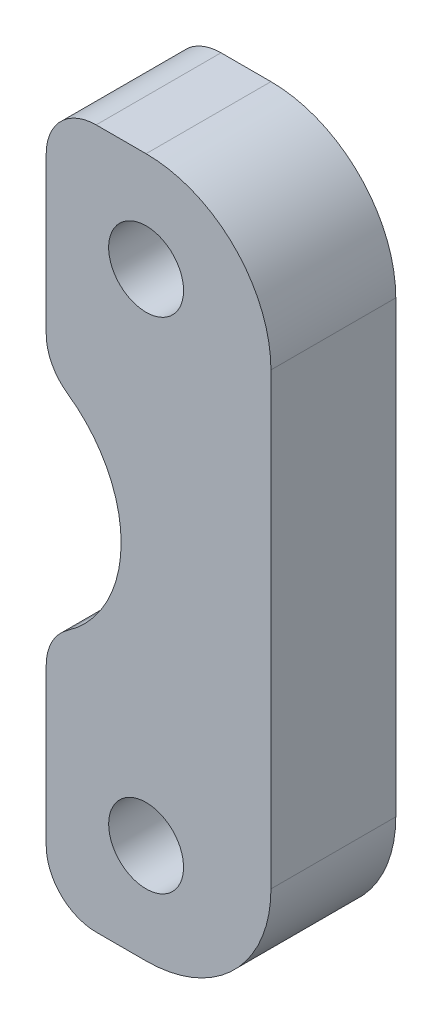
SolidWorks part; units mm, degrees
ref_plane "Plan de face" through (0, 0, 0) normal (0, 0, 1) x (1, 0, 0)
ref_plane "Plan de dessus" through (0, 0, 0) normal (0, 1, 0) x (1, 0, 0)
ref_plane "Plan de droite" through (0, 0, 0) normal (1, 0, 0) x (0, 0, -1)
sketch "Esquisse1" plane through (0, 0, 0) normal (0, 0, 1) x (1, 0, 0)
  line L0 (0, 0) -> (13.8043, 0) construction
  line L1 (0, 0) -> (0, 13.7674) construction
  line L2 (2, 19.222) -> (2, -18.3576) construction
  line L3 (2, 14) -> (2, 4.5826)
  line L4 (2, -14) -> (2, -4.5826)
  line L5 (2, 14) -> (11, 14)
  line L6 (11, 14) -> (11, -14)
  line L7 (11, -14) -> (2, -14)
  circle A0 centre (6, 10) radius 1.5
  circle A1 centre (6, -10) radius 1.5
  circle A2 centre (0, 0) radius 5 construction
  arc A3 (2, 4.5826) -> (2, -4.5826) centre (0, 0) cw
  dimension "D1" = 3
  dimension "D4" = 10
  dimension "D2" = 20
  dimension "D3" = 6
  dimension "D5" = 2
  dimension "D6" = 5
  dimension "D7" = 4
extrude "Boss.-Extru.1" add sketch "Esquisse1" along normal blind 5
fillet "Congé1" radius 5 2 edges at (11, -14, 2.5) (11, 14, 2.5)
fillet "Congé2" radius 2 4 edges at (2, -14, 2.5) (2, -4.5826, 2.5) (2, 4.5826, 2.5) (2, 14, 2.5)
